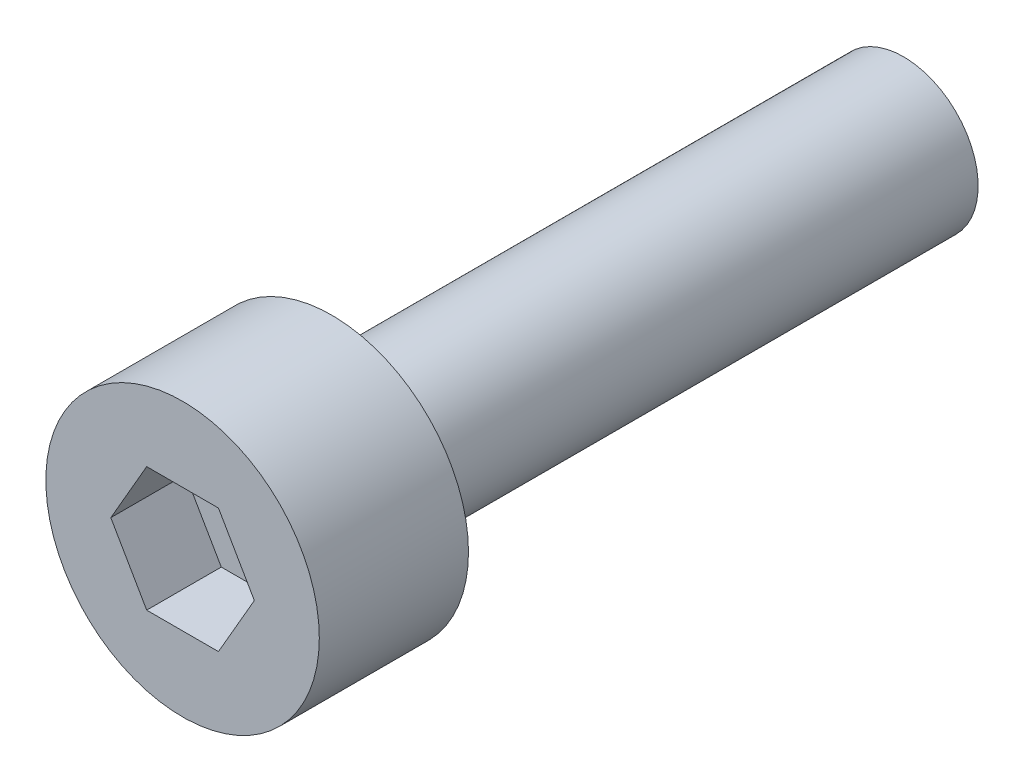
SolidWorks part; units mm, degrees
ref_plane "Front Plane" through (0, 0, 0) normal (0, 0, 1) x (1, 0, 0)
ref_plane "Top Plane" through (0, 0, 0) normal (0, 1, 0) x (1, 0, 0)
ref_plane "Right Plane" through (0, 0, 0) normal (1, 0, 0) x (0, 0, -1)
sketch "Sketch2" plane through (0, 0, 0) normal (0, 0, 1) x (1, 0, 0)
  circle A0 centre (0, 0) radius 2.75
  dimension "D1" = 5.5
extrude "Boss-Extrude1" add sketch "Sketch2" along normal blind 3
sketch "Sketch3" plane through (0, 0, 0) normal (0, 0, -1) x (-1, 0, 0)
  circle A0 centre (0, 0) radius 1.5
extrude "Boss-Extrude2" add sketch "Sketch3" along normal up to surface (11.5 mm away)
sketch "Sketch4" plane through (0, 0, 3) normal (0, 0, 1) x (1, 0, 0)
  line L1 (1.4434, 0) -> (0.7217, 1.25)
  line L2 (0.7217, 1.25) -> (-0.7217, 1.25)
  line L3 (-0.7217, 1.25) -> (-1.4434, 0)
  line L4 (-1.4434, 0) -> (-0.7217, -1.25)
  line L5 (-0.7217, -1.25) -> (0.7217, -1.25)
  line L6 (0.7217, -1.25) -> (1.4434, 0)
  circle A0 centre (0, 0) radius 1.25 construction
  dimension "D1" = 2.5
extrude "Cut-Extrude1" cut sketch "Sketch4" against normal blind 1.5
